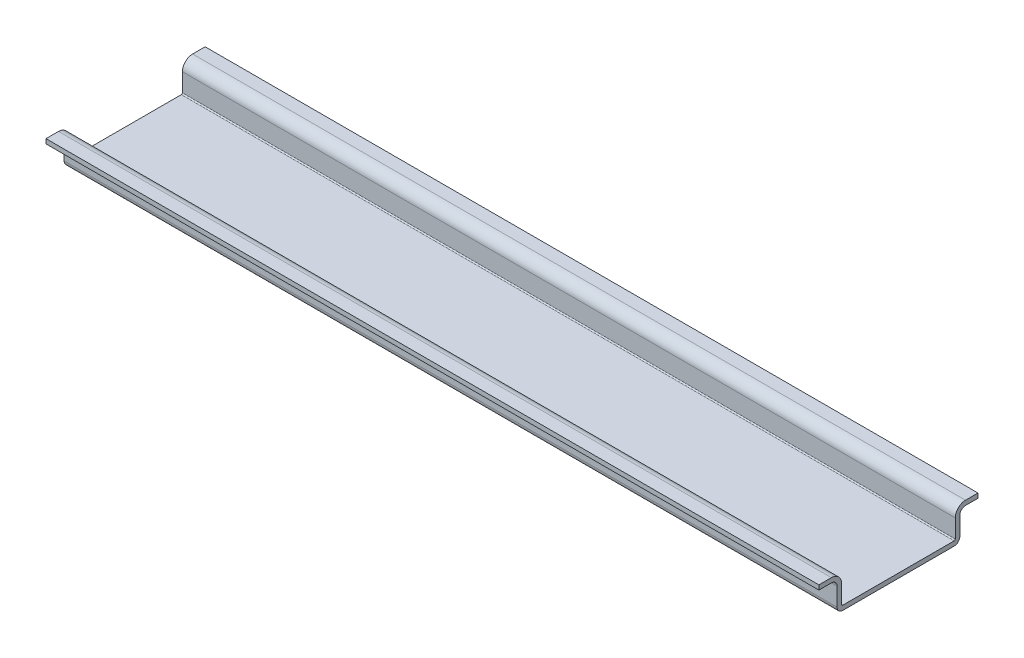
SolidWorks part; units mm, degrees
ref_plane "Front Plane" through (0, 0, 0) normal (0, 0, 1) x (1, 0, 0)
ref_plane "Top Plane" through (0, 0, 0) normal (0, 1, 0) x (1, 0, 0)
ref_plane "Right Plane" through (0, 0, 0) normal (1, 0, 0) x (0, 0, -1)
sketch3d "3DSketch1"
  line L0 (-85, 0, 0) -> (85, 0, 0)
  point P4 (0, 0, 0)
  dimension "D1" = 170
other "Omega TS-35(1)"
ref_plane "Plane1" through (-85, 0, 0) normal (1, 0, 0) x (0, 0, -1)
sketch "Sketch2" plane through (-85, 0, 0) normal (1, 0, 0) x (0, 0, -1)
  line L0 (12.25, 0) -> (-12.25, 0)
  line L1 (13.5, 1.25) -> (13.5, 5.25)
  line L2 (14.75, 6.5) -> (17.5, 6.5)
  line L3 (-14.75, 6.5) -> (-17.5, 6.5)
  line L4 (-13.5, 1.25) -> (-13.5, 5.25)
  line L5 (14.75, 7.5) -> (17.5, 7.5)
  line L6 (12.5, 1.25) -> (12.5, 5.25)
  line L7 (12.25, 1) -> (-12.25, 1)
  line L8 (-12.5, 1.25) -> (-12.5, 5.25)
  line L9 (-14.75, 7.5) -> (-17.5, 7.5)
  line L10 (17.5, 6.5) -> (17.5, 7.5)
  line L11 (-17.5, 6.5) -> (-17.5, 7.5)
  arc A0 (13.5, 5.25) -> (14.75, 6.5) centre (14.75, 5.25) cw
  arc A1 (-14.75, 6.5) -> (-13.5, 5.25) centre (-14.75, 5.25) cw
  arc A2 (-12.25, 0) -> (-13.5, 1.25) centre (-12.25, 1.25) cw
  arc A3 (12.25, 0) -> (13.5, 1.25) centre (12.25, 1.25) ccw
  arc A4 (12.5, 5.25) -> (14.75, 7.5) centre (14.75, 5.25) cw
  arc A5 (12.25, 1) -> (12.5, 1.25) centre (12.25, 1.25) ccw
  arc A6 (-12.25, 1) -> (-12.5, 1.25) centre (-12.25, 1.25) cw
  arc A7 (-14.75, 7.5) -> (-12.5, 5.25) centre (-14.75, 5.25) cw
  point P2 (0, 0)
  point P29 (0, 0)
  point P30 (0, 0)
